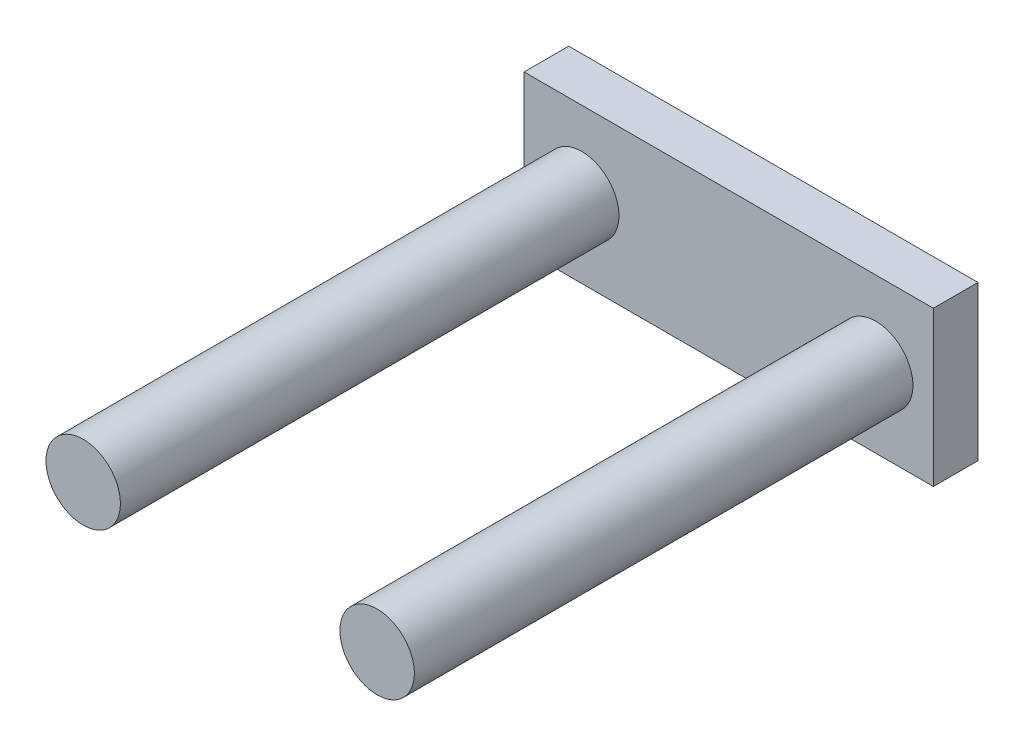
SolidWorks part; units mm, degrees
ref_plane "Alzado" through (0, 0, 0) normal (0, 0, 1) x (1, 0, 0)
ref_plane "Planta" through (0, 0, 0) normal (0, 1, 0) x (1, 0, 0)
ref_plane "Vista lateral" through (0, 0, 0) normal (1, 0, 0) x (0, 0, -1)
sketch "Croquis1" plane through (0, 0, 0) normal (0, 0, 1) x (1, 0, 0)
  line L1 (-55, -20.75) -> (55, -20.75)
  line L2 (-55, -20.75) -> (-55, 20.75)
  line L3 (-55, 20.75) -> (55, 20.75)
  line L4 (55, -20.75) -> (55, 20.75)
  line L5 (-55, -20.75) -> (55, 20.75) construction
  line L6 (-55, 20.75) -> (55, -20.75) construction
  point P0 (0, 0)
  dimension "D1" = 110
  dimension "D2" = 41.5
extrude "Saliente-Extruir1" add sketch "Croquis1" along normal blind 12
sketch "Croquis2" plane through (0, 0, 12) normal (0, 0, 1) x (1, 0, 0)
  line L0 (-55, 0) -> (-39.5, 0) construction
  line L1 (-55, 20.75) -> (-55, -20.75) construction
  line L2 (0, 20.75) -> (0, -20.75) construction
  line L3 (55, 20.75) -> (-55, 20.75) construction
  line L4 (-55, -20.75) -> (55, -20.75) construction
  circle A0 centre (-39.5, 0) radius 10
  circle A1 centre (39.5, 0) radius 10
  dimension "D2" = 20
  dimension "D1" = 15.5
extrude "Saliente-Extruir2" add sketch "Croquis2" along normal blind 134
